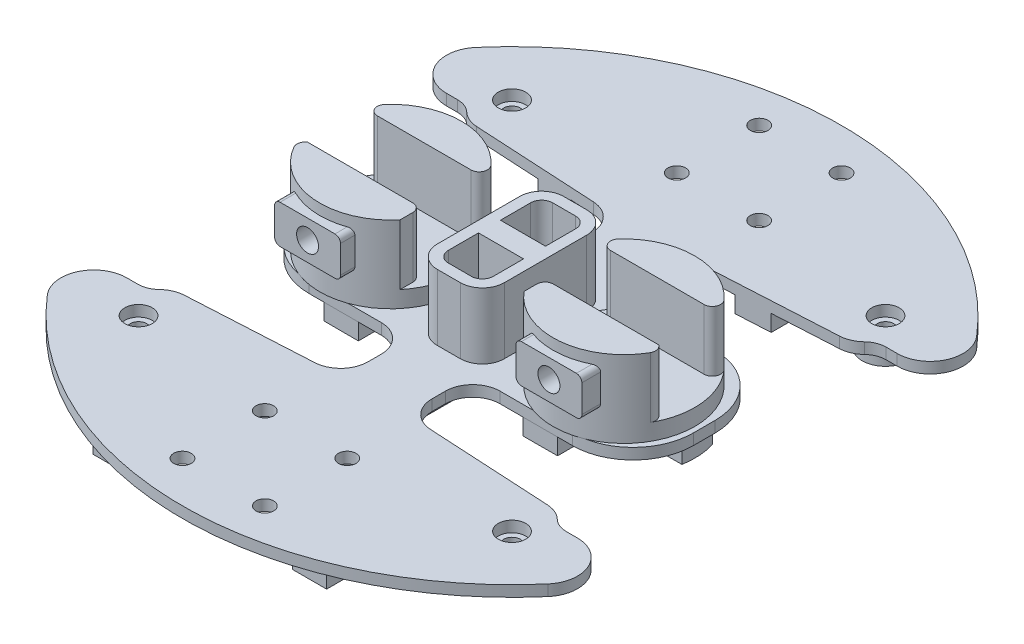
SolidWorks part; units mm, degrees
ref_plane "前视基准面" through (0, 0, 0) normal (0, 0, 1) x (1, 0, 0)
ref_plane "上视基准面" through (0, 0, 0) normal (0, 1, 0) x (1, 0, 0)
ref_plane "右视基准面" through (0, 0, 0) normal (1, 0, 0) x (0, 0, -1)
other "Configuration Table"
sketch "草图1" plane through (0, 0, 0) normal (0, 1, 0) x (1, 0, 0)
  line L0 (-39, -29.101) -> (-41.0356, -29.101)
  line L5 (-34, -34) -> (34, 34) construction
  line L6 (-34, 34) -> (34, -34) construction
  line L7 (-35, -25.101) -> (-35, 25.101)
  line L12 (35, -57.4674) -> (-27.6119, 45.3367) construction
  line L13 (27.6119, 45.3367) -> (-35, -57.4674) construction
  line L14 (35, -25.101) -> (35, 25.101)
  line L15 (39, -29.101) -> (41.0356, -29.101)
  line L16 (-39, 29.101) -> (-41.0356, 29.101)
  line L17 (39, 29.101) -> (41.0356, 29.101)
  circle A0 centre (-34, 34) radius 1.5
  circle A1 centre (-34, -34) radius 1.5
  circle A2 centre (34, -34) radius 1.5
  circle A3 centre (34, 34) radius 1.5
  arc A10 (45.5951, 39.0011) -> (-45.5951, 39.0011) centre (0, 0) ccw
  arc A11 (-45.5951, -39.0011) -> (45.5951, -39.0011) centre (0, 0) ccw
  arc A12 (45.5951, -39.0011) -> (41.0356, -29.101) centre (41.0356, -35.101) ccw
  arc A13 (41.0356, 29.101) -> (45.5951, 39.0011) centre (41.0356, 35.101) ccw
  arc A14 (-45.5951, 39.0011) -> (-41.0356, 29.101) centre (-41.0356, 35.101) ccw
  arc A15 (-45.5951, -39.0011) -> (-41.0356, -29.101) centre (-41.0356, -35.101) cw
  arc A16 (39, -29.101) -> (35, -25.101) centre (39, -25.101) cw
  arc A17 (35, 25.101) -> (39, 29.101) centre (39, 25.101) cw
  arc A18 (-35, -25.101) -> (-39, -29.101) centre (-39, -25.101) cw
  arc A19 (-35, 25.101) -> (-39, 29.101) centre (-39, 25.101) ccw
  point P0 (0, 0)
  point P17 (0, 0)
  point P23 (-35, 0)
  point P33 (-52.4703, -29.101)
  dimension "D1" = 6
  dimension "D2" = 4
extrude "凸台-拉伸1" add sketch "草图1" along normal blind 2
sketch "草图2" plane through (0, 2, 0) normal (0, 1, 0) x (1, 0, 0)
  line L5 (-0.0145, 59.9869) -> (-0.0145, -59.9869) construction
  line L6 (-58.924, 0) -> (58.895, 0) construction
  line L7 (-17.4337, 5.25) -> (-29.7603, 5.25)
  line L8 (-17.4337, -5.25) -> (-31.9827, -5.25)
  line L9 (-11.3, -6.75) -> (-11.3, -9.076)
  line L12 (-12.722, 5.25) -> (-17.4337, 5.25)
  line L13 (-12.8, -5.25) -> (-17.4337, -5.25)
  line L16 (12.7709, -5.25) -> (17.4046, -5.25)
  line L17 (12.6929, 5.25) -> (17.4046, 5.25)
  line L18 (11.2709, -6.75) -> (11.2709, -9.076)
  line L19 (17.4046, -5.25) -> (31.9536, -5.25)
  line L20 (17.4046, 5.25) -> (29.7312, 5.25)
  circle A9 centre (0, 0) radius 45 construction
  arc A10 (-11.3, -6.75) -> (-12.8, -5.25) centre (-12.8, -6.75) ccw
  arc A15 (-12.722, 5.25) -> (-11.602, 7.7478) centre (-12.722, 6.75) ccw
  arc A17 (-29.7603, 5.25) -> (-30.8803, 7.7478) centre (-29.7603, 6.75) cw
  arc A19 (-32.4521, -7.2411) -> (-31.9827, -5.25) centre (-31.1495, -6.4973) cw
  circle A22 centre (-21.2411, -0.8398) radius 12.9097
  circle A23 centre (21.2121, -0.8398) radius 12.9097
  arc A24 (32.423, -7.2411) -> (31.9536, -5.25) centre (31.1204, -6.4973) ccw
  arc A25 (29.7312, 5.25) -> (30.8512, 7.7478) centre (29.7312, 6.75) ccw
  arc A26 (12.6929, 5.25) -> (11.5729, 7.7478) centre (12.6929, 6.75) cw
  arc A27 (11.2709, -6.75) -> (12.7709, -5.25) centre (12.7709, -6.75) cw
extrude "凸台-拉伸2" add sketch "草图2" along normal blind 14 contours A15 A22 A17 L7 L12 | A19 A22 L9 A10 L13 L8 | A26 L17 L20 A25 A23 | A27 L18 A23 A24 L19 L16
sketch "草图3" plane through (0, 2, 0) normal (0, 1, 0) x (1, 0, 0)
  line L0 (-0.0145, 59.9869) -> (-0.0145, -59.9869) construction
  line L1 (-58.924, 0) -> (58.895, 0) construction
  line L2 (-17.4337, 5.25) -> (-29.7603, 5.25)
  line L3 (-17.4337, -5.25) -> (-31.9827, -5.25)
  line L4 (-11.3, -6.75) -> (-11.3, -9.076)
  line L5 (-12.722, 5.25) -> (-17.4337, 5.25)
  line L6 (-12.8, -5.25) -> (-17.4337, -5.25)
  line L7 (12.7709, -5.25) -> (17.4046, -5.25)
  line L8 (12.6929, 5.25) -> (17.4046, 5.25)
  line L9 (11.2709, -6.75) -> (11.2709, -9.076)
  line L10 (17.4046, -5.25) -> (31.9536, -5.25)
  line L11 (17.4046, 5.25) -> (29.7312, 5.25)
  circle A0 centre (0, 0) radius 45 construction
  arc A1 (-11.3, -6.75) -> (-12.8, -5.25) centre (-12.8, -6.75) ccw
  arc A2 (-12.722, 5.25) -> (-11.602, 7.7478) centre (-12.722, 6.75) ccw
  arc A3 (-29.7603, 5.25) -> (-30.8803, 7.7478) centre (-29.7603, 6.75) cw
  arc A4 (-32.4521, -7.2411) -> (-31.9827, -5.25) centre (-31.1495, -6.4973) cw
  circle A5 centre (-21.2411, -0.8398) radius 12.9097
  circle A6 centre (21.2121, -0.8398) radius 12.9097
  arc A7 (32.423, -7.2411) -> (31.9536, -5.25) centre (31.1204, -6.4973) ccw
  arc A8 (29.7312, 5.25) -> (30.8512, 7.7478) centre (29.7312, 6.75) ccw
  arc A9 (12.6929, 5.25) -> (11.5729, 7.7478) centre (12.6929, 6.75) cw
  arc A10 (11.2709, -6.75) -> (12.7709, -5.25) centre (12.7709, -6.75) cw
  arc M2 (11.2709, -6.75) -> (12.7709, -5.25) centre (12.7709, -6.75) cw
  line M3 (12.7709, -5.25) -> (31.9536, -5.25)
  arc M4 (31.9536, -5.25) -> (32.423, -7.2411) centre (31.1204, -6.4973) cw
  line M6 (11.2709, -9.076) -> (11.2709, -6.75)
  arc M7 (12.6929, 5.25) -> (11.5729, 7.7478) centre (12.6929, 6.75) cw
  arc M9 (30.8512, 7.7478) -> (29.7312, 5.25) centre (29.7312, 6.75) cw
  line M10 (29.7312, 5.25) -> (12.6929, 5.25)
  arc M11 (-32.4521, -7.2411) -> (-31.9827, -5.25) centre (-31.1495, -6.4973) cw
  line M12 (-31.9827, -5.25) -> (-12.8, -5.25)
  arc M13 (-12.8, -5.25) -> (-11.3, -6.75) centre (-12.8, -6.75) cw
  line M14 (-11.3, -6.75) -> (-11.3, -9.076)
  arc M29 (-11.602, 7.7478) -> (-12.722, 5.25) centre (-12.722, 6.75) cw
  line M30 (-12.722, 5.25) -> (-29.7603, 5.25)
  arc M31 (-29.7603, 5.25) -> (-30.8803, 7.7478) centre (-29.7603, 6.75) cw
extrude "凸台-拉伸3" add sketch "草图3" along normal blind 3 contours A5 M14 M29 M30 M31 M11 M12 M13 | A6 M6 M2 M3 M4 M9 M10 M7
sketch "草图4" plane through (0, 2, 0) normal (0, 1, 0) x (1, 0, 0)
  line L0 (-0.0145, 59.9869) -> (-0.0145, 1.9999) construction
  line L1 (-58.924, 0) -> (58.895, 0) construction
  line L2 (-0.0145, -1.9999) -> (-0.0145, -59.9869) construction
  line L7 (-2.1, -11.5) -> (2.1, -11.5)
  line L8 (-6.1, -7.5) -> (-6.1, 7.5)
  line L9 (-2.1, 11.5) -> (2.1, 11.5)
  line L10 (6.1, -7.5) -> (6.1, 7.5)
  line L13 (-6.1, -11.5) -> (6.1, 11.5) construction
  line L18 (-10, 55) -> (10, 35) construction
  line L19 (-10, 35) -> (10, 55) construction
  line L24 (-10, -55) -> (10, -35) construction
  line L25 (-10, -35) -> (10, -55) construction
  line L26 (-6.1, 11.5) -> (6.1, -11.5) construction
  line L27 (-2.1, -9.5) -> (2.1, -9.5)
  line L28 (-4.1, -7.5) -> (-4.1, -1.9999)
  line L29 (-2.1, 9.5) -> (2.1, 9.5)
  line L30 (4.1, -7.5) -> (4.1, -1.9999)
  line L31 (-4.1, -9.5) -> (4.1, 9.5) construction
  line L32 (-4.1, 9.5) -> (4.1, -9.5) construction
  line L33 (-0.0145, 1.9999) -> (4.1, 1.9999)
  line L34 (-0.0145, 1.9999) -> (-4.1, 1.9999)
  line L35 (4.1, 1.9999) -> (4.1, 7.5)
  line L36 (-0.0145, -1.9999) -> (4.1, -1.9999)
  line L37 (-0.0145, -1.9999) -> (-4.1, -1.9999)
  line L38 (-4.1, 1.9999) -> (-4.1, 7.5)
  line L39 (-0.0145, 0.0337) -> (-0.0145, -0.0337) construction
  circle A0 centre (0, 0) radius 45 construction
  arc A3 (6.1, -7.5) -> (2.1, -11.5) centre (2.1, -7.5) cw
  arc A4 (-2.1, -11.5) -> (-6.1, -7.5) centre (-2.1, -7.5) cw
  arc A5 (-2.1, 11.5) -> (-6.1, 7.5) centre (-2.1, 7.5) ccw
  arc A6 (2.1, 11.5) -> (6.1, 7.5) centre (2.1, 7.5) cw
  arc A7 (-2.1, -9.5) -> (-4.1, -7.5) centre (-2.1, -7.5) cw
  arc A8 (2.1, -9.5) -> (4.1, -7.5) centre (2.1, -7.5) ccw
  arc A9 (2.1, 9.5) -> (4.1, 7.5) centre (2.1, 7.5) cw
  arc A10 (-2.1, 9.5) -> (-4.1, 7.5) centre (-2.1, 7.5) ccw
  point P11 (0, 45)
  point P16 (0, -45)
  point P36 (6.1, 11.5)
  dimension "D1" = 4
  dimension "D2" = 2
extrude "凸台-拉伸4" add sketch "草图4" along normal blind 12 contours L8 A4 L7 A3 L10 A6 L9 A5 | L28 A10 L29 A9 L30 A8 L27 A7
sketch "草图5" plane through (0, 2, 0) normal (0, 1, 0) x (1, 0, 0)
  line L0 (35, -25.101) -> (35, 25.101) construction
  line L2 (0, -53.7742) -> (0, -45) construction
  line L6 (-35, 3) -> (-3, 3)
  line L7 (-35, 3) -> (-35, -3)
  line L8 (-3, -55) -> (3, -55)
  line L9 (-3, -55) -> (-3, -37)
  line L10 (-3, 55) -> (3, 55)
  line L11 (3, -55) -> (3, -37)
  line L12 (-3, -55) -> (-2.4509, -44.9332) construction
  line L13 (-3, 55) -> (-2.4509, 44.9332) construction
  line L14 (-35, -3) -> (-3, -3)
  line L15 (35, 3) -> (35, -3)
  line L16 (3, -31) -> (3, -3)
  line L18 (-3, 37) -> (-31, 37)
  line L19 (31, -37) -> (3, -37)
  line L21 (31, -31) -> (3, -31)
  line L25 (31, 31) -> (3, 31)
  line L27 (31, 37) -> (3, 37)
  line L29 (3, -3) -> (35, -3)
  line L31 (2.4509, 44.9332) -> (3, 55) construction
  line L32 (3, 37) -> (3, 55)
  line L33 (-3, -31) -> (-31, -31)
  line L35 (3, 3) -> (35, 3)
  line L36 (-3, -31) -> (-3, -3)
  line L37 (-0.1636, -3) -> (0.1636, -3)
  line L38 (-3, 31) -> (-31, 31)
  line L40 (-3, 3) -> (-3, 31)
  line L42 (-3, 37) -> (-3, 55)
  line L44 (0, 45) -> (0, 53.7742) construction
  line L46 (-3, -37) -> (-31, -37)
  line L48 (3, 3) -> (3, 31)
  line L50 (2.4509, -44.9332) -> (3, -55) construction
  circle A0 centre (0, 0) radius 45 construction
  arc A4 (-31, 37) -> (-31, 31) centre (-34, 34) ccw
  arc A5 (31, 31) -> (31, 37) centre (34, 34) ccw
  arc A6 (31, -37) -> (31, -31) centre (34, -34) ccw
  arc A7 (-31, -31) -> (-31, -37) centre (-34, -34) ccw
  point P1 (0, 45)
  point P3 (0, -34)
  point P27 (0, 34)
extrude "凸台-拉伸5" add sketch "草图5" against normal blind 5
sketch "草图6" plane through (0, 2, 0) normal (0, 1, 0) x (1, 0, 0)
  circle A0 centre (-34, 34) radius 2.5
  circle A1 centre (34, 34) radius 2.5
  circle A2 centre (34, -34) radius 2.5
  circle A3 centre (-34, -34) radius 2.5
extrude "切除-拉伸1" cut sketch "草图6" against normal blind 2
sketch "草图7" plane through (0, 2, 0) normal (0, 1, 0) x (1, 0, 0)
  line L0 (-53.4983, 0) -> (53.4983, 0) construction
  line L5 (-7.5, 37.5) -> (7.5, 52.5) construction
  line L6 (-7.5, 52.5) -> (7.5, 37.5) construction
  line L7 (-7.5, -52.5) -> (7.5, -37.5) construction
  line L8 (-7.5, -37.5) -> (7.5, -52.5) construction
  circle A0 centre (7.5, 52.5) radius 1.6
  circle A1 centre (7.5, 37.5) radius 1.6
  circle A2 centre (-7.5, 37.5) radius 1.6
  circle A3 centre (-7.5, 52.5) radius 1.6
  circle A4 centre (-7.5, -52.5) radius 1.6
  circle A5 centre (-7.5, -37.5) radius 1.6
  circle A6 centre (7.5, -37.5) radius 1.6
  circle A7 centre (7.5, -52.5) radius 1.6
  point P0 (0, 45)
  point P14 (0, 0)
  point P23 (0, -45)
extrude "切除-拉伸2" cut sketch "草图7" against normal through all
sketch "草图8" plane through (0, -3, 0) normal (0, -1, 0) x (1, 0, 0)
  circle A0 centre (-7.5, 37.5) radius 4.001
  circle A1 centre (7.5, 37.5) radius 4
  circle A2 centre (-7.5, -37.5) radius 4
  circle A3 centre (7.5, -37.5) radius 4
extrude "切除-拉伸3" cut sketch "草图8" against normal blind 3
sketch "草图9" plane through (0, 2, 0) normal (0, 1, 0) x (1, 0, 0)
  line L0 (-10.5358, 25.3606) -> (-33.0534, 26.6036)
  line L1 (-49.1208, 0) -> (49.1208, 0) construction
  line L2 (-48.2594, 29.101) -> (-35, 1.9876)
  line L5 (-24, 12.9876) -> (-10.8102, 12.9876)
  line L6 (-5.8332, 20.3912) -> (-5.8332, 17.9645)
  line L8 (-39, 29.101) -> (-48.2594, 29.101)
  line L9 (-39, -29.101) -> (-48.2594, -29.101)
  line L10 (-10.5358, -25.3606) -> (-33.0534, -26.6036)
  line L11 (-5.8332, -20.3912) -> (-5.8332, -17.9645)
  line L12 (-24, -12.9876) -> (-10.8102, -12.9876)
  line L13 (-48.2594, -29.101) -> (-35, -1.9876)
  line L14 (0, -62.0533) -> (0, 62.0533) construction
  line L15 (10.5358, -25.3606) -> (33.0534, -26.6036)
  line L16 (5.8332, -20.3912) -> (5.8332, -17.9645)
  line L17 (24, -12.9876) -> (10.8102, -12.9876)
  line L18 (48.2594, -29.101) -> (35, -1.9876)
  line L19 (39, -29.101) -> (48.2594, -29.101)
  line L20 (39, 29.101) -> (48.2594, 29.101)
  line L21 (10.5358, 25.3606) -> (33.0534, 26.6036)
  line L22 (5.8332, 20.3912) -> (5.8332, 17.9645)
  line L23 (24, 12.9876) -> (10.8102, 12.9876)
  line L24 (48.2594, 29.101) -> (35, 1.9876)
  arc A1 (-10.8102, 12.9876) -> (-5.8332, 17.9645) centre (-10.8102, 17.9645) ccw
  arc A2 (-5.8332, 20.3912) -> (-10.5358, 25.3606) centre (-10.8102, 20.3912) ccw
  arc A3 (-35, 1.9876) -> (-24, 12.9876) centre (-24, 1.9876) cw
  arc A4 (-36.228, 27.9848) -> (-39, 29.101) centre (-39, 25.101) ccw
  arc A5 (-33.0534, 26.6036) -> (-36.228, 27.9848) centre (-32.7791, 31.573) cw
  arc A6 (-36.228, -27.9848) -> (-39, -29.101) centre (-39, -25.101) cw
  arc A7 (-33.0534, -26.6036) -> (-36.228, -27.9848) centre (-32.7791, -31.573) ccw
  arc A8 (-5.8332, -20.3912) -> (-10.5358, -25.3606) centre (-10.8102, -20.3912) cw
  arc A9 (-10.8102, -12.9876) -> (-5.8332, -17.9645) centre (-10.8102, -17.9645) cw
  arc A10 (-35, -1.9876) -> (-24, -12.9876) centre (-24, -1.9876) ccw
  arc A11 (36.228, -27.9848) -> (39, -29.101) centre (39, -25.101) ccw
  arc A12 (33.0534, -26.6036) -> (36.228, -27.9848) centre (32.7791, -31.573) cw
  arc A13 (5.8332, -20.3912) -> (10.5358, -25.3606) centre (10.8102, -20.3912) ccw
  arc A14 (10.8102, -12.9876) -> (5.8332, -17.9645) centre (10.8102, -17.9645) ccw
  arc A15 (35, -1.9876) -> (24, -12.9876) centre (24, -1.9876) cw
  arc A16 (36.228, 27.9848) -> (39, 29.101) centre (39, 25.101) cw
  arc A17 (33.0534, 26.6036) -> (36.228, 27.9848) centre (32.7791, 31.573) ccw
  arc A18 (5.8332, 20.3912) -> (10.5358, 25.3606) centre (10.8102, 20.3912) cw
  arc A19 (10.8102, 12.9876) -> (5.8332, 17.9645) centre (10.8102, 17.9645) cw
  arc A20 (35, 1.9876) -> (24, 12.9876) centre (24, 1.9876) ccw
  point P24 (0, 0)
  point P42 (0, 0)
  dimension "D1" = 11
  dimension "D2" = 4.977
extrude "切除-拉伸4" cut sketch "草图9" against normal blind 12
sketch "草图10" plane through (0, -3, 0) normal (0, -1, 0) x (1, 0, 0)
  line L0 (-21.2495, 12.9504) -> (-21.2495, -12.9876)
  line L5 (-21.2495, 25.952) -> (-15, 25.607)
  line L6 (-15, 55) -> (-21.2495, 55)
  line L7 (-15, 55) -> (-15, 25.607)
  line L8 (-15, -55) -> (-21.2495, -55)
  line L9 (-21.2495, 55) -> (-21.2495, 25.952)
  line L11 (-21.2495, 12.9504) -> (-15, 12.9783)
  line L13 (-21.2495, -12.9876) -> (-15, -12.9876)
  line L15 (-21.2495, -25.952) -> (-15, -25.607)
  line L17 (-15, 12.9783) -> (-15, -12.9876)
  line L18 (-15, -25.607) -> (-15, -55)
  line L19 (-21.2495, -25.952) -> (-21.2495, -55)
  line L20 (0, -58.516) -> (0, 58.516) construction
  line L21 (21.2495, -25.952) -> (21.2495, -55)
  line L22 (15, -25.607) -> (15, -55)
  line L23 (15, 12.9783) -> (15, -12.9876)
  line L24 (21.2495, -25.952) -> (15, -25.607)
  line L25 (21.2495, -12.9876) -> (15, -12.9876)
  line L26 (21.2495, 12.9504) -> (15, 12.9783)
  line L27 (21.2495, 55) -> (21.2495, 25.952)
  line L28 (15, -55) -> (21.2495, -55)
  line L29 (15, 55) -> (15, 25.607)
  line L30 (15, 55) -> (21.2495, 55)
  line L31 (21.2495, 25.952) -> (15, 25.607)
  line L32 (21.2495, 12.9504) -> (21.2495, -12.9876)
  point P14 (0, 0)
extrude "凸台-拉伸6" add sketch "草图10" against normal blind 3
sketch "草图12" plane through (0, 0, 5.25) normal (0, 0, -1) x (-1, 0, 0)
  line L0 (11.3, 16) -> (32.6495, 16)
  line L1 (32.6495, 5) -> (32.6495, 16) construction
  line L2 (32.6495, 16) -> (31.9827, 16) construction
  line L3 (21.9747, 16) -> (21.9747, 5.05)
  line L5 (0, 0) -> (0, 13.025) construction
  line L6 (26.9747, 7.025) -> (16.9747, 7.025)
  line L7 (27.9747, 8.025) -> (27.9747, 13.025)
  line L8 (26.9747, 14.025) -> (16.9747, 14.025)
  line L9 (15.9747, 8.025) -> (15.9747, 13.025)
  line L10 (27.9747, 7.025) -> (15.9747, 14.025) construction
  line L11 (27.9747, 14.025) -> (15.9747, 7.025) construction
  line L12 (-26.9747, 14.025) -> (-16.9747, 14.025)
  line L13 (-15.9747, 8.025) -> (-15.9747, 13.025)
  line L14 (-26.9747, 7.025) -> (-16.9747, 7.025)
  line L15 (-27.9747, 8.025) -> (-27.9747, 13.025)
  line L16 (-27.9747, 14.025) -> (-15.9747, 7.025) construction
  line L17 (-27.9747, 7.025) -> (-15.9747, 14.025) construction
  arc A0 (27.9747, 13.025) -> (26.9747, 14.025) centre (26.9747, 13.025) ccw
  arc A1 (26.9747, 7.025) -> (27.9747, 8.025) centre (26.9747, 8.025) ccw
  arc A2 (16.9747, 7.025) -> (15.9747, 8.025) centre (16.9747, 8.025) cw
  arc A3 (16.9747, 14.025) -> (15.9747, 13.025) centre (16.9747, 13.025) ccw
  arc A4 (-16.9747, 14.025) -> (-15.9747, 13.025) centre (-16.9747, 13.025) cw
  arc A5 (-16.9747, 7.025) -> (-15.9747, 8.025) centre (-16.9747, 8.025) ccw
  arc A6 (-27.9747, 13.025) -> (-26.9747, 14.025) centre (-26.9747, 13.025) cw
  arc A7 (-26.9747, 7.025) -> (-27.9747, 8.025) centre (-26.9747, 8.025) cw
  point P9 (21.9747, 10.525)
  dimension "D1" = 1
extrude "凸台-拉伸7" add sketch "草图12" against normal blind 10 contours A7 L14 A5 L13 A4 L12 A6 L15 | L6 A1 L7 A0 L8 L3 | L8 A3 L9 A2 L6 L3
sketch "草图14" plane through (0, 0, 5.25) normal (0, 0, -1) x (-1, 0, 0)
  line L0 (-27.9747, 14.025) -> (-15.9747, 7.025) construction
  line L1 (27.9747, 14.025) -> (15.9747, 7.025) construction
  circle A0 centre (-21.9747, 10.525) radius 2
  circle A1 centre (21.9747, 10.525) radius 2
extrude "切除-拉伸5" cut sketch "草图14" against normal blind 12 contours A0 | A1
